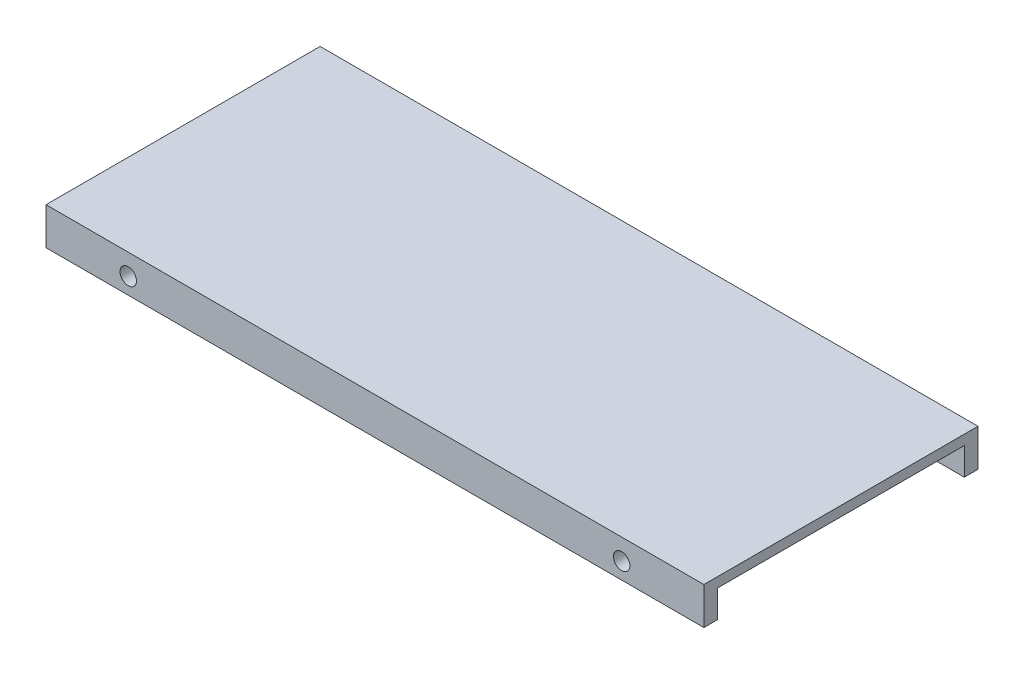
SolidWorks part; units mm, degrees
ref_plane "Front Plane" through (0, 0, 0) normal (0, 0, 1) x (1, 0, 0)
ref_plane "Top Plane" through (0, 0, 0) normal (0, 1, 0) x (1, 0, 0)
ref_plane "Right Plane" through (0, 0, 0) normal (1, 0, 0) x (0, 0, -1)
sketch "Sketch1" plane through (0, 0, 0) normal (0, 1, 0) x (1, 0, 0)
  line L1 (0, 0) -> (1200, 0)
  line L2 (0, 0) -> (0, 500)
  line L3 (0, 500) -> (1200, 500)
  line L4 (1200, 0) -> (1200, 500)
  dimension "D1" = 1200
  dimension "D2" = 500
extrude "Boss-Extrude1" add sketch "Sketch1" along normal blind 68
sketch "Sketch3" plane through (0, 0, 0) normal (0, 0, 1) x (1, 0, 0)
  line L0 (0, 68) -> (0, 0) construction
  line L1 (0, 0) -> (1200, 0) construction
  circle A0 centre (150, 30) radius 15
  dimension "D1" = 30
  dimension "D2" = 150
  dimension "D3" = 30
extrude "Cut-Extrude2" cut sketch "Sketch3" against normal through all
sketch "Sketch4" plane through (0, 0, -500) normal (0, 0, -1) x (-1, 0, 0)
  line L0 (-1200, 68) -> (-1200, 0) construction
  line L1 (-1200, 0) -> (0, 0) construction
  circle A0 centre (-1050, 30) radius 15
  point P4 (-1200, 34)
  dimension "D1" = 30
  dimension "D2" = 150
  dimension "D3" = 30
extrude "Cut-Extrude3" cut sketch "Sketch4" against normal through all
sketch "Sketch2" plane through (0, 0, 0) normal (0, -1, 0) x (1, 0, 0)
  line L0 (0, 0) -> (1200, 0) construction
  line L1 (0, -25) -> (1200, -25)
  line L2 (0, -25) -> (0, -475)
  line L3 (0, -475) -> (1200, -475)
  line L4 (1200, -25) -> (1200, -475)
  line L5 (0, -500) -> (0, 0) construction
  dimension "D1" = 1200
  dimension "D2" = 450
  dimension "D3" = 25
  dimension "D4" = 0
extrude "Cut-Extrude1" cut sketch "Sketch2" against normal blind 50
